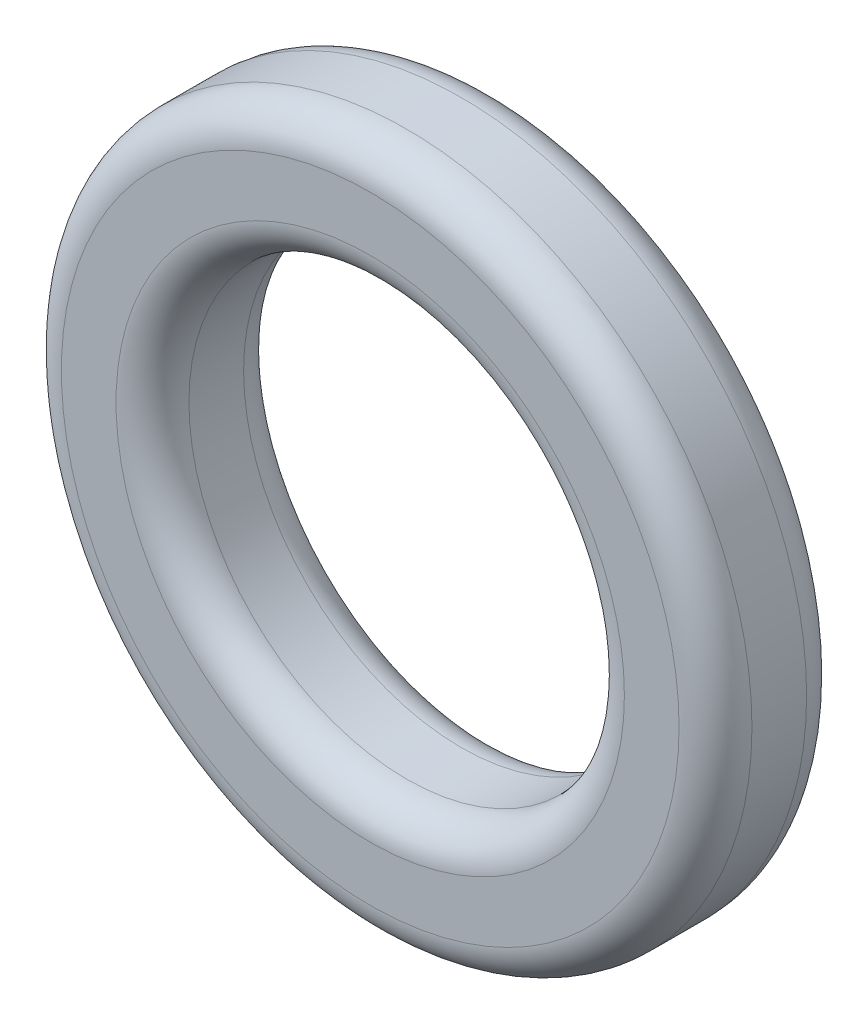
SolidWorks part; units mm, degrees
ref_plane "Front Plane" through (0, 0, 0) normal (0, 0, 1) x (1, 0, 0)
ref_plane "Top Plane" through (0, 0, 0) normal (0, 1, 0) x (1, 0, 0)
ref_plane "Right Plane" through (0, 0, 0) normal (1, 0, 0) x (0, 0, -1)
sketch "Sketch2" plane through (0, 0, 0) normal (0, 0, 1) x (1, 0, 0)
  circle A0 centre (0, 0) radius 3.0353
  circle A1 centre (0, 0) radius 4.8133
  dimension "D1" = 9.6266
  dimension "D2" = 6.0706
extrude "Boss-Extrude1" add sketch "Sketch2" along normal blind 1.778
fillet "Fillet1" radius 0.508 4 edges at (3.0353, 0, 0) (4.8133, 0, 0) (3.0353, 0, 1.778) (4.8133, 0, 1.778)
